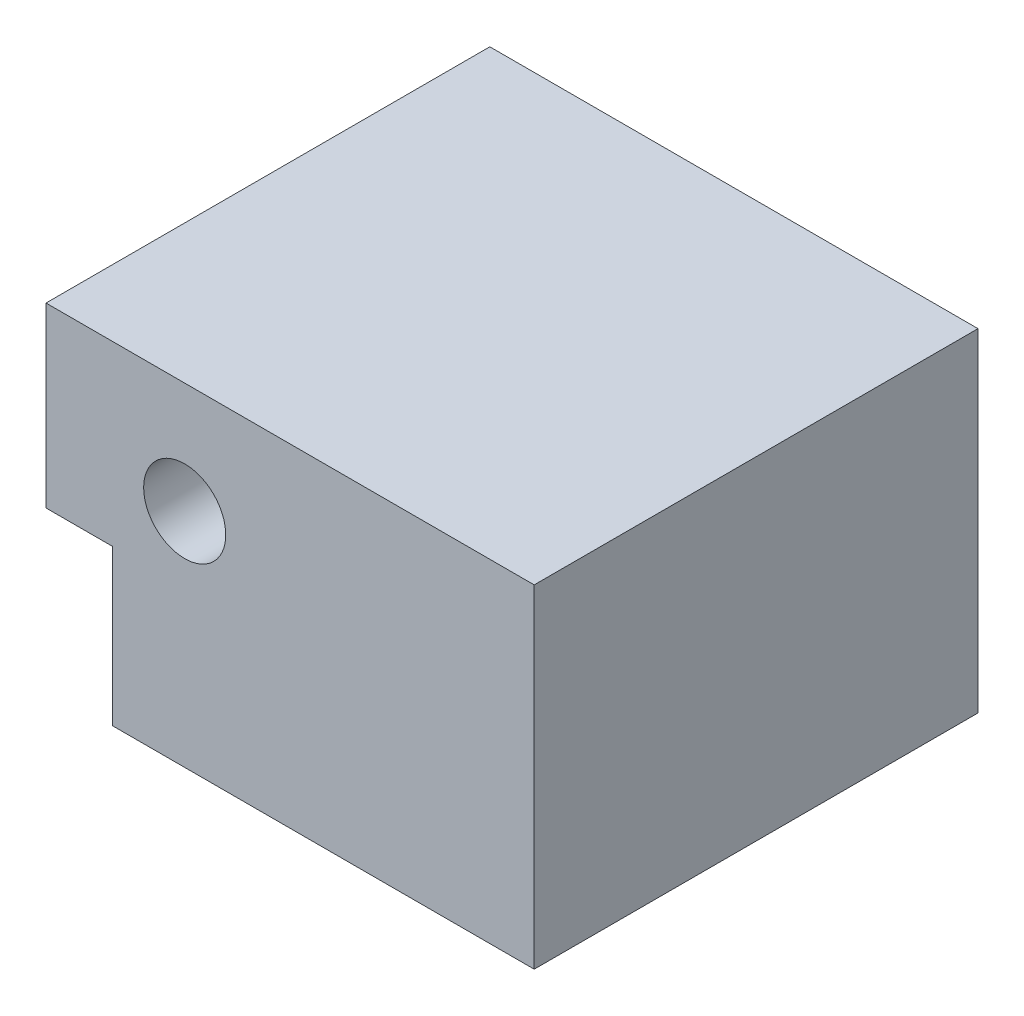
SolidWorks part; units mm, degrees
ref_plane "Front Plane" through (0, 0, 0) normal (0, 0, 1) x (1, 0, 0)
ref_plane "Top Plane" through (0, 0, 0) normal (0, 1, 0) x (1, 0, 0)
ref_plane "Right Plane" through (0, 0, 0) normal (1, 0, 0) x (0, 0, -1)
sketch "Sketch2" plane through (0, 0, 0) normal (0, 1, 0) x (1, 0, 0)
  line L0 (0, 10) -> (0, -10) construction
  line L1 (-9.5, -10) -> (9.5, -10)
  line L2 (-9.5, -10) -> (-9.5, 10)
  line L3 (-9.5, 10) -> (9.5, 10)
  line L4 (9.5, -10) -> (9.5, 10)
  point P6 (0, 0)
  dimension "D1" = 19
  dimension "D2" = 20
extrude "Boss-Extrude1" add sketch "Sketch2" along normal mid plane 15
hole_wizard "Ø3.7 (3.7) Diameter Hole2" positions "Sketch5" profile "Sketch6" hole size "Ø3.7" standard "ANSI Metric"
sketch "Sketch5" plane through (-9.5, 0, 0) normal (-1, 0, 0) x (0, 0, 1)
  point P0 (-5, -3.5)
  point P2 (5, -3.5)
sketch "Sketch6" plane through (-9.5, -3.5, -5) normal (0, 1, 0) x (0, 0, 1)
  line L0 (0, 0) -> (0, 12.7116)
  line L1 (0, 12.7116) -> (1.85, 11.6)
  line L2 (1.85, 11.6) -> (1.85, 0)
  line L5 (1.85, 0) -> (0, 0)
  line L10 (0, 12.7116) -> (-1.85, 11.6) construction
  line L11 (0, -6.35) -> (0, 107.95) construction
  dimension "Hole Dia." = 3.7
  dimension "Hole Depth" = 11.6
  dimension "Drill Angle" = 118
sketch "Sketch10" plane through (-9.5, 0, 0) normal (-1, 0, 0) x (0, 0, 1)
  line L0 (10, 7.5) -> (10, -7.5) construction
  line L1 (-10, 7.5) -> (10, 7.5)
  line L2 (-10, 7.5) -> (-10, -0.5)
  line L3 (-10, -0.5) -> (10, -0.5)
  line L4 (10, 7.5) -> (10, -0.5)
  dimension "D1" = 8
extrude "Boss-Extrude2" add sketch "Sketch10" along normal blind 3
hole_wizard "Ø3.7 (3.7) Diameter Hole1" positions "Sketch8" profile "Sketch9" hole size "Ø3.7" standard "ANSI Metric" end condition through all
sketch "Sketch8" plane through (0, 0, -10) normal (0, 0, -1) x (-1, 0, 0)
  line L7 (-9.5, 7.5) -> (12.5, 7.5) construction
  line L8 (12.5, 7.5) -> (12.5, -0.5) construction
  point P2 (6.25, 2.5)
  dimension "D1" = 6.25
  dimension "D2" = 5
sketch "Sketch9" plane through (-6.25, 2.5, -10) normal (1, 0, 0) x (0, 1, 0)
  line L0 (0, 0) -> (0, 20)
  line L1 (0, 20) -> (1.85, 20)
  line L2 (1.85, 20) -> (1.85, 0)
  line L5 (1.85, 0) -> (0, 0)
  line L11 (0, -6.35) -> (0, 107.95) construction
  dimension "Thru Hole Dia." = 3.7
  dimension "Thru Hole Depth" = 20
